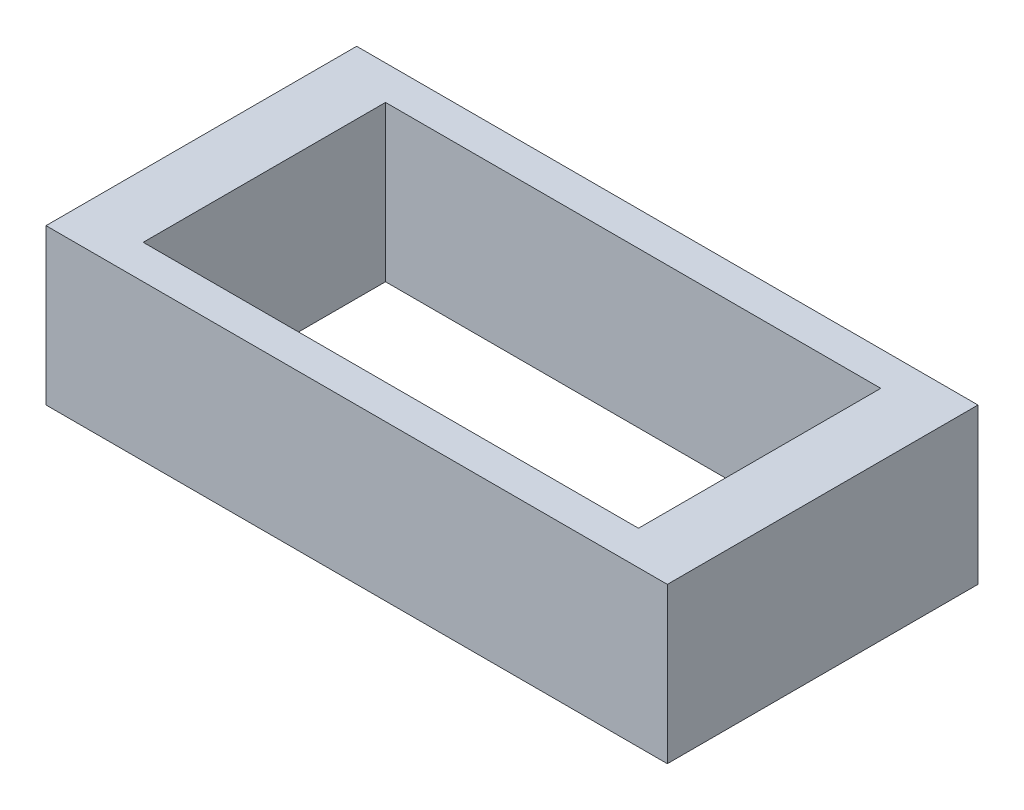
SolidWorks part; units mm, degrees
ref_plane "Front Plane" through (0, 0, 0) normal (0, 0, 1) x (1, 0, 0)
ref_plane "Top Plane" through (0, 0, 0) normal (0, 1, 0) x (1, 0, 0)
ref_plane "Right Plane" through (0, 0, 0) normal (1, 0, 0) x (0, 0, -1)
sketch "Sketch1" plane through (0, 0, 0) normal (0, 1, 0) x (1, 0, 0)
  line L0 (0, 0) -> (50.8, 0)
  line L1 (0, 0) -> (0, 25.4)
  line L2 (0, 25.4) -> (50.8, 25.4)
  line L3 (50.8, 25.4) -> (50.8, 0)
  line L4 (5.1543, 22.606) -> (5.1543, 2.794)
  line L7 (5.1543, 22.606) -> (45.6457, 22.606)
  line L8 (45.6457, 22.606) -> (45.6457, 2.794)
  line L9 (45.6457, 2.794) -> (5.1543, 2.794)
  dimension "D1" = 50.8
  dimension "D2" = 25.4
  dimension "D3" = 19.812
  dimension "D4" = 40.4914
  dimension "D5" = 2.794
  dimension "D6" = 5.1543
extrude "Boss-Extrude1" add sketch "Sketch1" along normal blind 12.7
